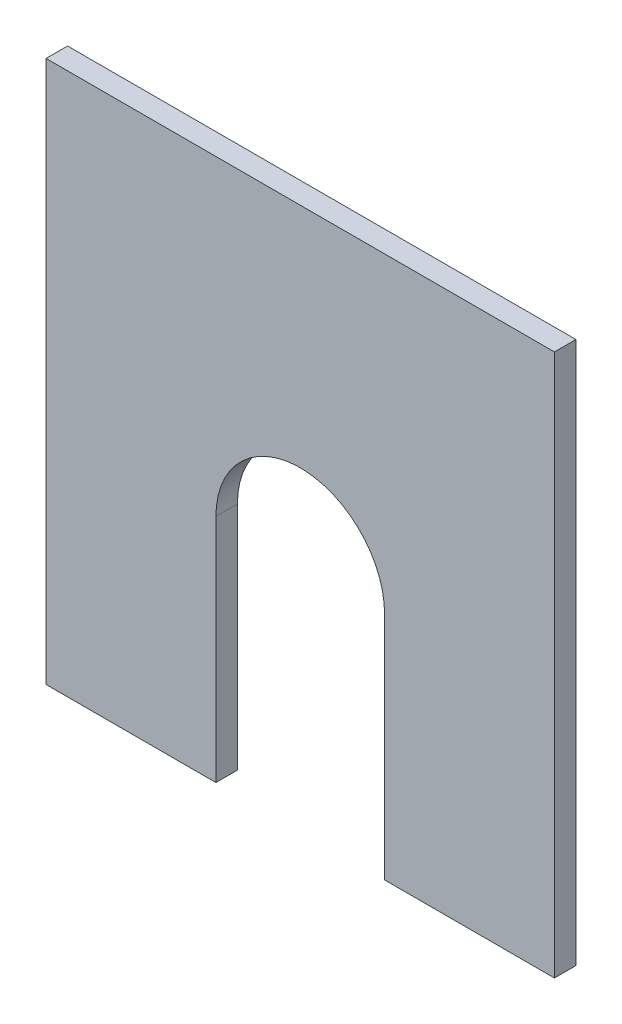
SolidWorks part; units mm, degrees
ref_plane "Front Plane" through (0, 0, 0) normal (0, 0, 1) x (1, 0, 0)
ref_plane "Top Plane" through (0, 0, 0) normal (0, 1, 0) x (1, 0, 0)
ref_plane "Right Plane" through (0, 0, 0) normal (1, 0, 0) x (0, 0, -1)
sketch "Sketch1" plane through (0, 0, 0) normal (0, 0, 1) x (1, 0, 0)
  line L0 (-75, 80) -> (75, -80) construction
  line L1 (-75, 80) -> (75, 80)
  line L2 (-75, 80) -> (-75, -80)
  line L3 (-75, -80) -> (75, -80)
  line L4 (75, 80) -> (75, -80)
  point P0 (0, 0)
  point P6 (0, 0)
  dimension "D1" = 150
  dimension "D2" = 160
extrude "Boss-Extrude1" add sketch "Sketch1" along normal blind 6.35
sketch "Sketch2" plane through (0, 0, 6.35) normal (0, 0, 1) x (1, 0, 0)
  line L0 (0, -12) -> (0, -47.5) construction
  line L1 (-24.89, -12) -> (-24.89, -80)
  line L2 (24.89, -12) -> (24.89, -80)
  line L3 (-75, -80) -> (75, -80) construction
  line L4 (-24.89, -80) -> (24.89, -80)
  arc A1 (-24.89, -12) -> (24.89, -12) centre (0, -12) cw
  dimension "D1" = 35.5
  dimension "D3" = 24.89
  dimension "D4" = 68
extrude "Cut-Extrude1" cut sketch "Sketch2" against normal up to next
